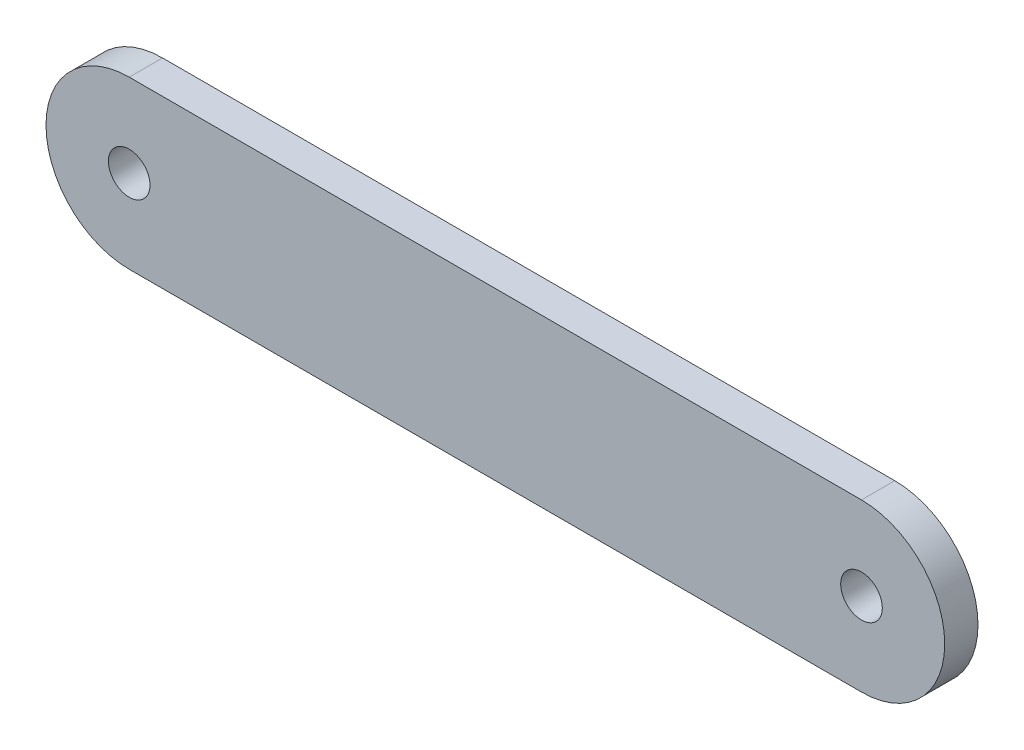
SolidWorks part; units mm, degrees
material "Alloy Steel"
ref_plane "Front Plane" through (0, 0, 0) normal (0, 0, 1) x (1, 0, 0)
ref_plane "Top Plane" through (0, 0, 0) normal (0, 1, 0) x (1, 0, 0)
ref_plane "Right Plane" through (0, 0, 0) normal (1, 0, 0) x (0, 0, -1)
other "Configuration Table"
sketch "Sketch2" plane through (0, 0, 0) normal (0, 0, 1) x (1, 0, 0)
  line L0 (0, 0) -> (44, 0) construction
  line L1 (0, 5) -> (44, 5)
  line L2 (0, -5) -> (44, -5)
  arc A0 (0, 5) -> (0, -5) centre (0, 0) ccw
  arc A1 (44, -5) -> (44, 5) centre (44, 0) ccw
  circle A2 centre (0, 0) radius 1.25
  circle A3 centre (44, 0) radius 1.25
  point P3 (22, 0)
  dimension "D2" = 2.5
  dimension "D1" = 44
  dimension "D3" = 10
extrude "Boss-Extrude1" add sketch "Sketch2" along normal blind 2
sketch3d "3DSketch1"
  line L0 (44, 0, 2) -> (44, 0, 0) construction
  point P0 (44, 0, 2)
ref_point "Point1"
ref_point "Point2"
ref_point "Point3"
